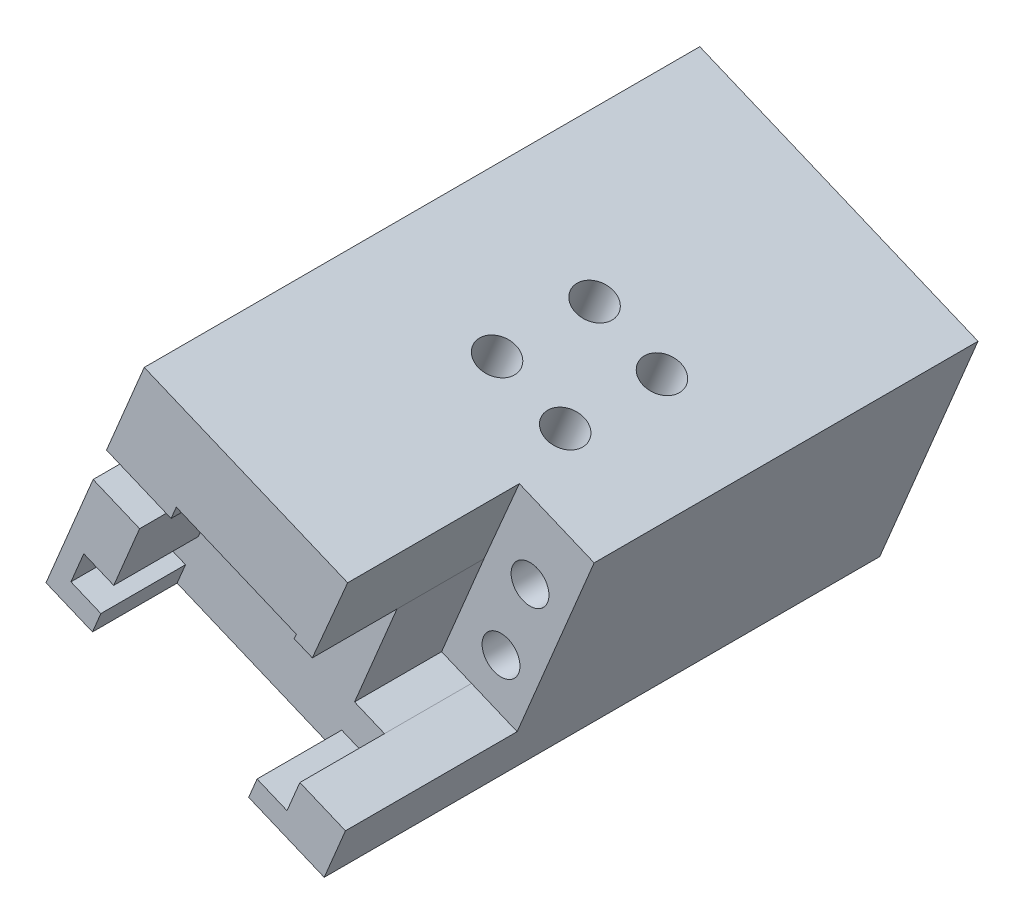
SolidWorks part; units mm, degrees
ref_plane "Front Plane" through (0, 0, 0) normal (0, 0, 1) x (1, 0, 0)
ref_plane "Top Plane" through (0, 0, 0) normal (0, 1, 0) x (1, 0, 0)
ref_plane "Right Plane" through (0, 0, 0) normal (1, 0, 0) x (0, 0, -1)
sketch "Sketch1" plane through (0, 0, 0) normal (0, 0, 1) x (1, 0, 0)
  line L0 (-68.5273, 69.9322) -> (-69.2968, 68.0868)
  line L1 (-69.2968, 68.0868) -> (-71.9733, 69.2031)
  line L2 (-71.9733, 69.2031) -> (-77.7829, 55.2704)
  line L3 (-77.7829, 55.2704) -> (-82.213, 57.1181)
  line L4 (-82.213, 57.1181) -> (-84.1139, 52.5593)
  line L5 (-84.1139, 52.5593) -> (-79.6838, 50.7115)
  line L6 (-79.6838, 50.7115) -> (-80.9269, 47.7304)
  line L9 (-57.8157, 38.0936) -> (-56.5735, 41.0726)
  line L10 (-56.5735, 41.0726) -> (-52.1435, 39.2249)
  line L11 (-52.1435, 39.2249) -> (-50.2426, 43.7837)
  line L12 (-50.2426, 43.7837) -> (-54.6726, 45.6315)
  line L13 (-54.6726, 45.6315) -> (-48.4014, 60.6714)
  line L14 (-48.4014, 60.6714) -> (-51.0779, 61.7878)
  line L15 (-51.0779, 61.7878) -> (-50.7701, 62.5259)
  line L16 (-50.7701, 62.5259) -> (-68.5273, 69.9322)
  line L17 (-67.844, 68.2711) -> (-68.6135, 66.4257)
  line L18 (-68.6135, 66.4257) -> (-71.29, 67.5421)
  line L19 (-71.29, 67.5421) -> (-77.0995, 53.6093)
  line L20 (-77.0995, 53.6093) -> (-81.5296, 55.457)
  line L21 (-81.5296, 55.457) -> (-82.453, 53.2426)
  line L22 (-82.453, 53.2426) -> (-78.0229, 51.3948)
  line L23 (-78.0229, 51.3948) -> (-79.6773, 47.4272)
  line L24 (-79.6773, 47.4272) -> (-73.9551, 45.0406)
  line L25 (-73.9551, 45.0406) -> (-58.9113, 38.7661)
  line L26 (-58.9113, 38.7661) -> (-57.2569, 42.7337)
  line L27 (-57.2569, 42.7337) -> (-52.8268, 40.886)
  line L28 (-52.8268, 40.886) -> (-51.9035, 43.1004)
  line L29 (-51.9035, 43.1004) -> (-56.3335, 44.9482)
  line L30 (-56.3335, 44.9482) -> (-50.0623, 59.9881)
  line L31 (-50.0623, 59.9881) -> (-52.7388, 61.1045)
  line L32 (-52.7388, 61.1045) -> (-52.431, 61.8426)
  line L33 (-52.431, 61.8426) -> (-67.844, 68.2711)
  line L34 (-67.844, 68.2711) -> (-68.6135, 66.4257) construction
  line L35 (-68.6135, 66.4257) -> (-71.29, 67.5421) construction
  line L36 (-71.29, 67.5421) -> (-77.0995, 53.6093) construction
  line L37 (-77.0995, 53.6093) -> (-81.5296, 55.457) construction
  line L38 (-81.5296, 55.457) -> (-82.453, 53.2426) construction
  line L39 (-82.453, 53.2426) -> (-78.0229, 51.3948) construction
  line L40 (-78.0229, 51.3948) -> (-79.6773, 47.4272) construction
  line L41 (-79.6773, 47.4272) -> (-73.9551, 45.0406) construction
  line L43 (-58.9113, 38.7661) -> (-57.2569, 42.7337) construction
  line L44 (-57.2569, 42.7337) -> (-52.8268, 40.886) construction
  line L45 (-52.8268, 40.886) -> (-51.9035, 43.1004) construction
  line L46 (-51.9035, 43.1004) -> (-56.3335, 44.9482) construction
  line L47 (-56.3335, 44.9482) -> (-50.0623, 59.9881) construction
  line L48 (-50.0623, 59.9881) -> (-52.7388, 61.1045) construction
  line L49 (-52.7388, 61.1045) -> (-52.431, 61.8426) construction
  line L50 (-52.431, 61.8426) -> (-67.844, 68.2711) construction
  line L51 (-73.2676, 85.4604) -> (-87.8042, 50.598)
  line L52 (-73.2676, 85.4604) -> (-27.6179, 66.4257)
  line L53 (-87.8042, 50.598) -> (-80.9269, 47.7304)
  line L54 (-27.6179, 66.4257) -> (-42.1546, 31.5633)
  line L55 (-79.6838, 50.7115) -> (-81.3382, 46.7439) construction
  line L56 (-81.3382, 46.7439) -> (-74.444, 43.8685) construction
  line L57 (-58.2279, 37.105) -> (-56.5735, 41.0726) construction
  line L58 (-74.444, 43.8685) -> (-58.2279, 37.105) construction
  line L59 (-57.8157, 38.0936) -> (-42.1546, 31.5633)
  line L60 (-73.9551, 45.0406) -> (-58.9113, 38.7661) construction
  dimension "D1" = 0
extrude "Boss-Extrude1" add sketch "Sketch1" along normal blind 15.6968 contours L54 L59 L9 L10 L11 L12 L13 L14 L15 L16 L0 L1 L2 L3 L4 L5 L6 L53 L51 L52
ref_plane "Plane1" through (11.931, 28.6057, 24.6955) normal (0.3011, 0.7218, 0.6232) x (0.9536, -0.2238, -0.2014)
mirror "Mirror4" about plane through (0, 0, 0) normal (0, 0, -1) of "Boss-Extrude1"
sketch "Sketch6" plane through (-85.8949, 35.8158, 0) normal (0.923, -0.3849, 0) x (0, 0, -1)
  line L0 (-15.6968, 36.1735) -> (-15.6968, 21.078) construction
  line L1 (-2.286, 36.1735) -> (-15.6968, 36.1735)
  line L2 (-2.286, 36.1735) -> (-2.286, 31.0235)
  line L3 (-2.286, 31.0235) -> (-15.6968, 31.0235)
  line L4 (-15.6968, 36.1735) -> (-15.6968, 31.0235)
extrude "Cut-Extrude1" cut sketch "Sketch6" against normal blind 22.86
mirror "Mirror5" about plane through (0, 0, 0) normal (0, 0, 1) of "Cut-Extrude1"
ref_plane "Plane2" through (-0.5927, 3.8911, -3.0051) normal (0.0001, -0.9997, -0.0227) x (1, -0.0001, 0.0094)
ref_plane "Plane3" through (-0.5927, 3.8911, -3.0051) normal (-0.0094, -0.0227, 0.9997) x (1, -0.0001, 0.0094)
ref_plane "Plane4" through (-0.5927, 3.8911, -3.0051) normal (1, -0.0001, 0.0094) x (-0.0001, 0.9997, 0.0227)
sketch "Sketch8" plane through (0, 0, 0) normal (0, 0, 1) x (1, 0, 0)
  line L0 (-73.2676, 85.4604) -> (-87.8042, 50.598)
  line L1 (-73.2676, 85.4604) -> (-27.6179, 66.4257)
  line L2 (-87.8042, 50.598) -> (-42.1546, 31.5633)
  line L3 (-27.6179, 66.4257) -> (-42.1546, 31.5633)
  line L4 (-27.6179, 66.4257) -> (-42.1546, 31.5633) construction
extrude "Boss-Extrude7" add sketch "Sketch8" along normal mid plane 6.35
sketch "Sketch12" plane through (19.5047, 46.7769, 0) normal (0.3849, 0.923, 0) x (0.923, -0.3849, 0)
  circle A0 centre (-81.4859, 7.9685) radius 2.8
  circle A1 centre (-70.7087, -6.3235) radius 2.2479
  circle A2 centre (-70.7087, -6.3235) radius 2.2479 construction
  circle A3 centre (-81.4859, 7.9685) radius 2.2479
  circle A4 centre (-81.4859, 7.9685) radius 2.2479 construction
  circle A5 centre (-81.6322, -6.3235) radius 2.2479
  circle A6 centre (-81.6322, -6.3235) radius 2.2479 construction
  circle A7 centre (-70.5636, 7.8567) radius 2.2479
  circle A8 centre (-70.5636, 7.8567) radius 2.2479 construction
  circle A9 centre (-70.5636, 7.8567) radius 2.8
  circle A10 centre (-70.7087, -6.3235) radius 2.8
  circle A11 centre (-81.6322, -6.3235) radius 2.8
  dimension "D5" = 5.6
  dimension "D1" = 0
  dimension "D2" = 0
  dimension "D3" = 0
  dimension "D4" = 0
extrude "Cut-Extrude3" cut sketch "Sketch12" against normal blind 9.1
sketch "Sketch13" plane through (0, 0, 15.6968) normal (0, 0, 1) x (1, 0, 0)
  circle A0 centre (-45.8847, 49.5842) radius 2.8
  circle A1 centre (-41.59, 60.8099) radius 2.8
  dimension "D1" = 5.6
  dimension "D2" = 5.6
extrude "Cut-Extrude4" cut sketch "Sketch13" against normal blind 9.1
sketch "Sketch14" plane through (0, 0, 15.6968) normal (0, 0, 1) x (1, 0, 0)
  line L0 (-46.6408, 33.434) -> (-32.1041, 68.2964)
  line L1 (-46.6408, 33.434) -> (-39.9467, 30.6427)
  line L2 (-32.1041, 68.2964) -> (-25.41, 65.5051)
  line L3 (-39.9467, 30.6427) -> (-25.41, 65.5051)
  line L4 (-57.8157, 38.0936) -> (-42.1546, 31.5633) construction
  line L5 (-73.2676, 85.4604) -> (-27.6179, 66.4257) construction
extrude "Cut-Extrude6" cut sketch "Sketch14" against normal blind 98.762
sketch "Sketch15" plane through (4.968, 11.9145, 0) normal (-0.3849, -0.923, 0) x (0.923, -0.3849, 0)
  line L0 (-93.0629, 3.175) -> (-93.0629, -3.175) construction
  line L1 (-95.8826, 4.4897) -> (-95.8826, -2.7022) construction
  circle A0 centre (-95.8826, 0) radius 3.175
  point P9 (-93.0629, 0)
  dimension "D1" = 6.35
extrude "Boss-Extrude8" add sketch "Sketch15" along normal blind 19.05
sketch "Sketch17" plane through (0, 0, 15.6968) normal (0, 0, 1) x (1, 0, 0)
  line L0 (-48.4014, 60.6714) -> (-43.1734, 72.912)
  line L1 (-50.2426, 43.7837) -> (-43.4979, 40.9714)
  line L9 (-77.7829, 55.2704) -> (-73.9553, 64.4498)
  line L10 (-73.9553, 64.4498) -> (-80.8327, 67.3175)
  line L11 (-80.8327, 67.3175) -> (-87.8042, 50.598)
  line L12 (-87.8042, 50.598) -> (-80.9269, 47.7304)
  line L13 (-80.9269, 47.7304) -> (-79.6838, 50.7115)
  line L14 (-79.6838, 50.7115) -> (-84.1139, 52.5593)
  line L15 (-84.1139, 52.5593) -> (-82.213, 57.1181)
  line L16 (-57.8157, 38.0936) -> (-46.6408, 33.434)
  line L17 (-46.6408, 33.434) -> (-32.1041, 68.2964)
  line L18 (-32.1041, 68.2964) -> (-73.2676, 85.4604)
  line L19 (-73.2676, 85.4604) -> (-78.8507, 72.0708)
  line L20 (-78.8507, 72.0708) -> (-71.9733, 69.2031)
  line L21 (-71.9733, 69.2031) -> (-69.2968, 68.0868)
  line L22 (-69.2968, 68.0868) -> (-68.5273, 69.9322)
  line L23 (-68.5273, 69.9322) -> (-50.7701, 62.5259)
  line L24 (-50.7701, 62.5259) -> (-51.0779, 61.7878)
  line L25 (-51.0779, 61.7878) -> (-48.4014, 60.6714)
  line L26 (-48.4014, 60.6714) -> (-54.6726, 45.6315)
  line L27 (-54.6726, 45.6315) -> (-50.2426, 43.7837)
  line L28 (-50.2426, 43.7837) -> (-52.1435, 39.2249)
  line L29 (-52.1435, 39.2249) -> (-56.5735, 41.0726)
  line L30 (-56.5735, 41.0726) -> (-57.8157, 38.0936)
  line L31 (-57.8157, 38.0936) -> (-46.6408, 33.434)
  line L32 (-46.6408, 33.434) -> (-43.4979, 40.9714)
  line L33 (-43.1734, 72.912) -> (-73.2676, 85.4604)
  line L34 (-73.2676, 85.4604) -> (-78.8507, 72.0708)
  line L35 (-78.8507, 72.0708) -> (-71.9733, 69.2031)
  line L36 (-71.9733, 69.2031) -> (-69.2968, 68.0868)
  line L37 (-69.2968, 68.0868) -> (-68.5273, 69.9322)
  line L38 (-68.5273, 69.9322) -> (-50.7701, 62.5259)
  line L39 (-50.7701, 62.5259) -> (-51.0779, 61.7878)
  line L40 (-51.0779, 61.7878) -> (-48.4014, 60.6714)
  line L42 (-54.6726, 45.6315) -> (-50.2426, 43.7837)
  line L43 (-50.2426, 43.7837) -> (-52.1435, 39.2249)
  line L44 (-52.1435, 39.2249) -> (-56.5735, 41.0726)
  line L45 (-56.5735, 41.0726) -> (-57.8157, 38.0936)
  line L46 (-82.213, 57.1181) -> (-77.7829, 55.2704)
  line L47 (-77.7829, 55.2704) -> (-73.9553, 64.4498)
  line L48 (-73.9553, 64.4498) -> (-80.8327, 67.3175)
  line L49 (-80.8327, 67.3175) -> (-87.8042, 50.598)
  line L50 (-87.8042, 50.598) -> (-80.9269, 47.7304)
  line L51 (-80.9269, 47.7304) -> (-79.6838, 50.7115)
  line L52 (-79.6838, 50.7115) -> (-84.1139, 52.5593)
  line L53 (-84.1139, 52.5593) -> (-82.213, 57.1181)
  line L54 (-82.213, 57.1181) -> (-77.7829, 55.2704)
  line M26 (-57.8157, 38.0936) -> (-46.6408, 33.434)
  line M27 (-46.6408, 33.434) -> (-32.1041, 68.2964)
  line M28 (-32.1041, 68.2964) -> (-73.2676, 85.4604)
  line M29 (-73.2676, 85.4604) -> (-78.8507, 72.0708)
  line M30 (-78.8507, 72.0708) -> (-71.9733, 69.2031)
  line M31 (-71.9733, 69.2031) -> (-69.2968, 68.0868)
  line M32 (-69.2968, 68.0868) -> (-68.5273, 69.9322)
  line M33 (-68.5273, 69.9322) -> (-50.7701, 62.5259)
  line M34 (-50.7701, 62.5259) -> (-51.0779, 61.7878)
  line M35 (-51.0779, 61.7878) -> (-48.4014, 60.6714)
  line M38 (-50.2426, 43.7837) -> (-52.1435, 39.2249)
  line M39 (-52.1435, 39.2249) -> (-56.5735, 41.0726)
  line M40 (-56.5735, 41.0726) -> (-57.8157, 38.0936)
  dimension "D1" = 0
  dimension "D2" = 0
extrude "Boss-Extrude9" add sketch "Sketch17" along normal blind 25.4 contours L0 M35 M28 M29 M30 M31 M32 M33 M34 | L53 L54 L47 L48 L49 L50 L51 L52 | L1 M38 M39 M40 M26 M27
sketch "Sketch18" plane through (0, 0, 3.175) normal (0, 0, 1) x (1, 0, 0)
  line L19 (-79.6838, 50.7115) -> (-80.9269, 47.7304)
  line L20 (-80.9269, 47.7304) -> (-57.8157, 38.0936)
  line L21 (-57.8157, 38.0936) -> (-56.5735, 41.0726)
  line L22 (-56.5735, 41.0726) -> (-52.1435, 39.2249)
  line L23 (-52.1435, 39.2249) -> (-50.2426, 43.7837)
  line L24 (-50.2426, 43.7837) -> (-54.6726, 45.6315)
  line L25 (-54.6726, 45.6315) -> (-48.4014, 60.6714)
  line L26 (-48.4014, 60.6714) -> (-51.0779, 61.7878)
  line L27 (-51.0779, 61.7878) -> (-50.7701, 62.5259)
  line L28 (-50.7701, 62.5259) -> (-68.5273, 69.9322)
  line L29 (-68.5273, 69.9322) -> (-69.2968, 68.0868)
  line L30 (-69.2968, 68.0868) -> (-71.9733, 69.2031)
  line L31 (-71.9733, 69.2031) -> (-78.8507, 72.0708)
  line L32 (-78.8507, 72.0708) -> (-80.8327, 67.3175)
  line L33 (-80.8327, 67.3175) -> (-73.9553, 64.4498)
  line L34 (-73.9553, 64.4498) -> (-77.7829, 55.2704)
  line L35 (-77.7829, 55.2704) -> (-82.213, 57.1181)
  line L36 (-82.213, 57.1181) -> (-84.1139, 52.5593)
  line L37 (-84.1139, 52.5593) -> (-79.6838, 50.7115)
  line L38 (-79.6838, 50.7115) -> (-80.9269, 47.7304)
  line L39 (-80.9269, 47.7304) -> (-57.8157, 38.0936)
  line L40 (-57.8157, 38.0936) -> (-56.5735, 41.0726)
  line L41 (-56.5735, 41.0726) -> (-52.1435, 39.2249)
  line L42 (-52.1435, 39.2249) -> (-50.2426, 43.7837)
  line L43 (-50.2426, 43.7837) -> (-54.6726, 45.6315)
  line L44 (-54.6726, 45.6315) -> (-48.4014, 60.6714)
  line L45 (-48.4014, 60.6714) -> (-51.0779, 61.7878)
  line L46 (-51.0779, 61.7878) -> (-50.7701, 62.5259)
  line L47 (-50.7701, 62.5259) -> (-68.5273, 69.9322)
  line L48 (-68.5273, 69.9322) -> (-69.2968, 68.0868)
  line L49 (-69.2968, 68.0868) -> (-71.9733, 69.2031)
  line L50 (-71.9733, 69.2031) -> (-78.8507, 72.0708)
  line L51 (-78.8507, 72.0708) -> (-80.8327, 67.3175)
  line L52 (-80.8327, 67.3175) -> (-73.9553, 64.4498)
  line L53 (-73.9553, 64.4498) -> (-77.7829, 55.2704)
  line L54 (-77.7829, 55.2704) -> (-82.213, 57.1181)
  line L55 (-82.213, 57.1181) -> (-84.1139, 52.5593)
  line L56 (-84.1139, 52.5593) -> (-79.6838, 50.7115)
  dimension "D1" = 0
extrude "Boss-Extrude10" add sketch "Sketch18" along normal blind 25.4
mirror "Mirror6" about plane through (0, 0, 0) normal (0, 0, 1) of "Boss-Extrude10", "Boss-Extrude9"
sketch "Sketch19" plane through (0, 0, -15.6968) normal (0, 0, -1) x (-1, 0, 0)
  line L6 (43.4979, 40.9714) -> (50.2426, 43.7837)
  line L7 (50.2426, 43.7837) -> (54.6726, 45.6315)
  line L8 (54.6726, 45.6315) -> (48.4014, 60.6714)
  line L9 (48.4014, 60.6714) -> (43.1734, 72.912)
  line L10 (43.1734, 72.912) -> (32.1041, 68.2964)
  line L11 (32.1041, 68.2964) -> (43.4979, 40.9714)
  line L12 (43.4979, 40.9714) -> (50.2426, 43.7837)
  line L13 (50.2426, 43.7837) -> (54.6726, 45.6315)
  line L14 (54.6726, 45.6315) -> (48.4014, 60.6714)
  line L15 (48.4014, 60.6714) -> (43.1734, 72.912)
  line L16 (43.1734, 72.912) -> (32.1041, 68.2964)
  line L17 (32.1041, 68.2964) -> (43.4979, 40.9714)
  dimension "D1" = 0
extrude "Boss-Extrude11" add sketch "Sketch19" along normal up to surface (25.4 mm away) up to face at (-61.7043, 69.1834, -41.0968)
sketch "Sketch20" plane through (-92.7723, 38.6835, 0) normal (-0.923, 0.3849, 0) x (0, 0, 1)
  line L1 (-5.1685, 41.5805) -> (-10.7685, 41.5805) construction
  line L2 (-22.2657, 44.8788) -> (-14.8315, 44.8788)
  line L3 (-22.2657, 44.8788) -> (-22.2657, 20.4212)
  line L4 (-22.2657, 20.4212) -> (-14.8315, 20.4212)
  line L5 (-14.8315, 44.8788) -> (-14.8315, 37.5175)
  line L6 (-14.8315, 20.4212) -> (20.6207, 20.4212)
  line L8 (-14.8315, 37.5175) -> (13.1865, 37.5175)
  line L9 (20.6207, 20.4212) -> (20.6207, 37.5175)
  line L11 (20.6207, 37.5175) -> (20.6207, 44.8788)
  line L12 (20.6207, 44.8788) -> (13.1865, 44.8788)
  line L13 (13.1865, 37.5175) -> (13.1865, 44.8788)
  line L14 (-5.1685, 41.5805) -> (-10.7685, 41.5805)
  line L15 (9.1235, 41.5805) -> (3.5235, 41.5805) construction
  line L16 (9.1235, 41.5805) -> (3.5235, 41.5805)
  line L17 (-10.7685, 41.5805) -> (-14.8315, 41.5805) construction
  line L18 (-14.8315, 41.5805) -> (-10.7685, 41.5805) construction
  line L19 (-10.7685, 41.5805) -> (-10.7685, 37.5175) construction
  line L20 (9.1235, 41.5805) -> (9.1235, 37.5175) construction
  line L21 (9.1235, 37.5175) -> (9.1235, 41.5805) construction
  line L22 (9.1235, 41.5805) -> (13.1865, 41.5805) construction
  line L23 (-28.575, 36.1735) -> (-22.2657, 36.1735) construction
  line L24 (-28.575, 36.1735) -> (-41.0968, 36.1735) construction
  line L25 (-28.575, 36.1735) -> (-28.575, 31.0235) construction
  line L26 (28.575, 36.1735) -> (20.6207, 36.1735) construction
  line L27 (-14.8315, 44.8788) -> (13.1865, 44.8788) construction
sketch "Sketch21" plane through (4.968, 11.9145, 0) normal (-0.3849, -0.923, 0) x (0.923, -0.3849, 0)
  line L0 (-100.5142, 41.0968) -> (-100.5142, -41.0968) construction
  line L1 (-100.5142, 8.0496) -> (-89.49, 8.0496)
  line L2 (-100.5142, 8.0496) -> (-100.5142, -10.0525)
  line L3 (-100.5142, -10.0525) -> (-89.49, -10.0525)
  line L4 (-89.49, 8.0496) -> (-89.49, -10.0525)
extrude "Boss-Extrude12" add sketch "Sketch21" along normal blind 6.604
